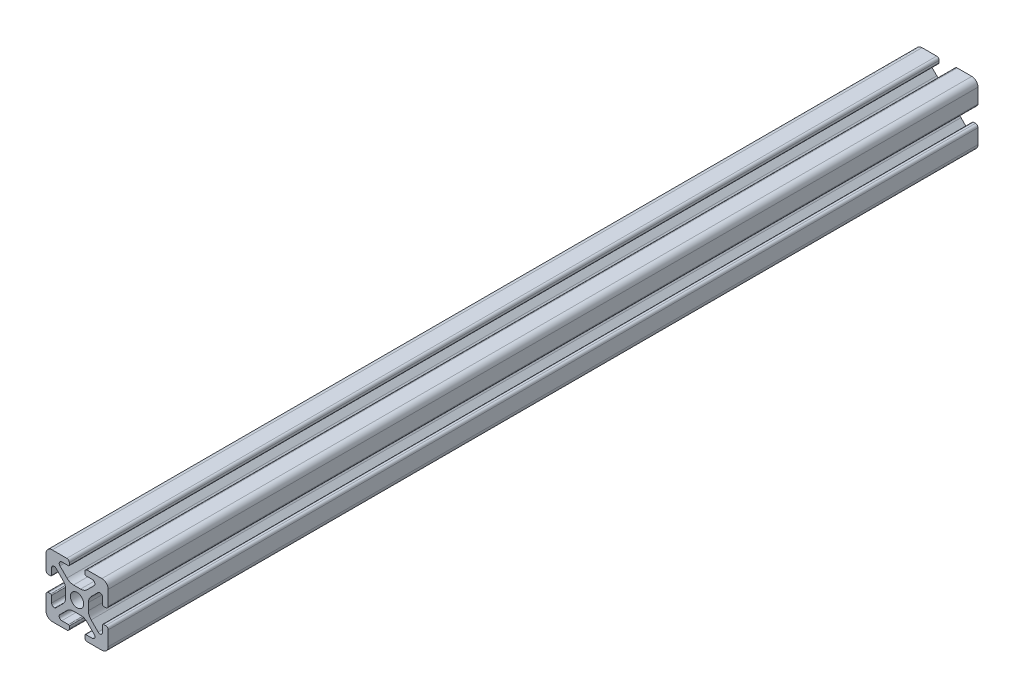
SolidWorks part; units mm, degrees
ref_plane "Plan de face" through (0, 0, 0) normal (0, 0, 1) x (1, 0, 0)
ref_plane "Plan de dessus" through (0, 0, 0) normal (0, 1, 0) x (1, 0, 0)
ref_plane "Plan de droite" through (0, 0, 0) normal (1, 0, 0) x (0, 0, -1)
ref_plane "Plan1" through (0, 0, 0) normal (0, 0, -1) x (-1, 0, 0)
sketch "Esquisse1" plane through (0, 0, 0) normal (0, 0, -1) x (-1, 0, 0)
  line L0 (-20, 6.7) -> (-20, 2)
  line L1 (-18, 0) -> (-13.3, 0)
  line L2 (-12.5, 0.8) -> (-12.5, 1.5)
  line L3 (-12.8, 1.8) -> (-14.9184, 1.8)
  line L4 (-15.5064, 3.2196) -> (-13.2547, 5.4713)
  line L5 (-11.1334, 6.35) -> (-8.8666, 6.35)
  line L6 (-6.7453, 5.4713) -> (-4.4936, 3.2196)
  line L7 (-5.0816, 1.8) -> (-7.2, 1.8)
  line L8 (-7.5, 1.5) -> (-7.5, 0.8)
  line L9 (-6.7, 0) -> (-2, 0)
  line L10 (0, 2) -> (0, 6.7)
  line L11 (-0.8, 7.5) -> (-1.5, 7.5)
  line L12 (-1.8, 7.2) -> (-1.8, 5.0816)
  line L13 (-3.2196, 4.4936) -> (-5.4713, 6.7453)
  line L14 (-6.35, 8.8666) -> (-6.35, 11.1334)
  line L15 (-5.4713, 13.2547) -> (-3.2196, 15.5064)
  line L16 (-1.8, 14.9184) -> (-1.8, 12.8)
  line L17 (-1.5, 12.5) -> (-0.8, 12.5)
  line L18 (0, 13.3) -> (0, 18)
  line L19 (-2, 20) -> (-6.7, 20)
  line L20 (-7.5, 19.2) -> (-7.5, 18.5)
  line L21 (-7.2, 18.2) -> (-5.0816, 18.2)
  line L22 (-4.4936, 16.7804) -> (-6.7453, 14.5287)
  line L23 (-8.8666, 13.65) -> (-11.1334, 13.65)
  line L24 (-13.2547, 14.5287) -> (-15.5064, 16.7804)
  line L25 (-14.9184, 18.2) -> (-12.8, 18.2)
  line L26 (-12.5, 18.5) -> (-12.5, 19.2)
  line L27 (-13.3, 20) -> (-18, 20)
  line L28 (-20, 18) -> (-20, 13.3)
  line L29 (-19.2, 12.5) -> (-18.5, 12.5)
  line L30 (-18.2, 12.8) -> (-18.2, 14.9184)
  line L31 (-16.7804, 15.5064) -> (-14.5287, 13.2547)
  line L32 (-13.65, 11.1334) -> (-13.65, 8.8666)
  line L33 (-14.5287, 6.7453) -> (-16.7804, 4.4936)
  line L34 (-18.2, 5.0816) -> (-18.2, 7.2)
  line L35 (-18.5, 7.5) -> (-19.2, 7.5)
  arc A0 (-19.2, 7.5) -> (-20, 6.7) centre (-19.2, 6.7) ccw
  arc A1 (-20, 2) -> (-18, 0) centre (-18, 2) ccw
  arc A2 (-13.3, 0) -> (-12.5, 0.8) centre (-13.3, 0.8) ccw
  arc A3 (-12.5, 1.5) -> (-12.8, 1.8) centre (-12.8, 1.5) ccw
  arc A4 (-14.9184, 1.8) -> (-15.5064, 3.2196) centre (-14.9184, 2.6316) cw
  arc A5 (-13.2547, 5.4713) -> (-11.1334, 6.35) centre (-11.1334, 3.35) cw
  arc A6 (-8.8666, 6.35) -> (-6.7453, 5.4713) centre (-8.8666, 3.35) cw
  arc A7 (-4.4936, 3.2196) -> (-5.0816, 1.8) centre (-5.0816, 2.6316) cw
  arc A8 (-7.2, 1.8) -> (-7.5, 1.5) centre (-7.2, 1.5) ccw
  arc A9 (-7.5, 0.8) -> (-6.7, 0) centre (-6.7, 0.8) ccw
  arc A10 (-2, 0) -> (0, 2) centre (-2, 2) ccw
  arc A11 (0, 6.7) -> (-0.8, 7.5) centre (-0.8, 6.7) ccw
  arc A12 (-1.5, 7.5) -> (-1.8, 7.2) centre (-1.5, 7.2) ccw
  arc A13 (-1.8, 5.0816) -> (-3.2196, 4.4936) centre (-2.6316, 5.0816) cw
  arc A14 (-5.4713, 6.7453) -> (-6.35, 8.8666) centre (-3.35, 8.8666) cw
  arc A15 (-6.35, 11.1334) -> (-5.4713, 13.2547) centre (-3.35, 11.1334) cw
  arc A16 (-3.2196, 15.5064) -> (-1.8, 14.9184) centre (-2.6316, 14.9184) cw
  arc A17 (-1.8, 12.8) -> (-1.5, 12.5) centre (-1.5, 12.8) ccw
  arc A18 (-0.8, 12.5) -> (0, 13.3) centre (-0.8, 13.3) ccw
  arc A19 (0, 18) -> (-2, 20) centre (-2, 18) ccw
  arc A20 (-6.7, 20) -> (-7.5, 19.2) centre (-6.7, 19.2) ccw
  arc A21 (-7.5, 18.5) -> (-7.2, 18.2) centre (-7.2, 18.5) ccw
  arc A22 (-5.0816, 18.2) -> (-4.4936, 16.7804) centre (-5.0816, 17.3684) cw
  arc A23 (-6.7453, 14.5287) -> (-8.8666, 13.65) centre (-8.8666, 16.65) cw
  arc A24 (-11.1334, 13.65) -> (-13.2547, 14.5287) centre (-11.1334, 16.65) cw
  arc A25 (-15.5064, 16.7804) -> (-14.9184, 18.2) centre (-14.9184, 17.3684) cw
  arc A26 (-12.8, 18.2) -> (-12.5, 18.5) centre (-12.8, 18.5) ccw
  arc A27 (-12.5, 19.2) -> (-13.3, 20) centre (-13.3, 19.2) ccw
  arc A28 (-18, 20) -> (-20, 18) centre (-18, 18) ccw
  arc A29 (-20, 13.3) -> (-19.2, 12.5) centre (-19.2, 13.3) ccw
  arc A30 (-18.5, 12.5) -> (-18.2, 12.8) centre (-18.5, 12.8) ccw
  arc A31 (-18.2, 14.9184) -> (-16.7804, 15.5064) centre (-17.3684, 14.9184) cw
  arc A32 (-14.5287, 13.2547) -> (-13.65, 11.1334) centre (-16.65, 11.1334) cw
  arc A33 (-13.65, 8.8666) -> (-14.5287, 6.7453) centre (-16.65, 8.8666) cw
  arc A34 (-16.7804, 4.4936) -> (-18.2, 5.0816) centre (-17.3684, 5.0816) cw
  arc A35 (-18.2, 7.2) -> (-18.5, 7.5) centre (-18.5, 7.2) ccw
  circle A36 centre (-10, 10) radius 2.15
extrude "Boss.-Extru.1" add sketch "Esquisse1" against normal blind 280
